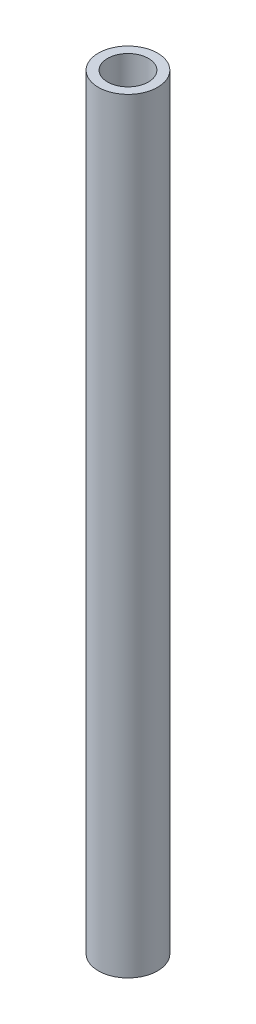
SolidWorks part; units mm, degrees
ref_plane "Front Plane" through (0, 0, 0) normal (0, 0, 1) x (1, 0, 0)
ref_plane "Top Plane" through (0, 0, 0) normal (0, 1, 0) x (1, 0, 0)
ref_plane "Right Plane" through (0, 0, 0) normal (1, 0, 0) x (0, 0, -1)
sketch "Sketch1" plane through (0, 0, 0) normal (0, 1, 0) x (1, 0, 0)
  circle A0 centre (0, 0) radius 4.7625
  circle A1 centre (0, 0) radius 3.2893
  dimension "D1" = 9.525
  dimension "D2" = 6.5786
extrude "Boss-Extrude1" add sketch "Sketch1" along normal blind 123
